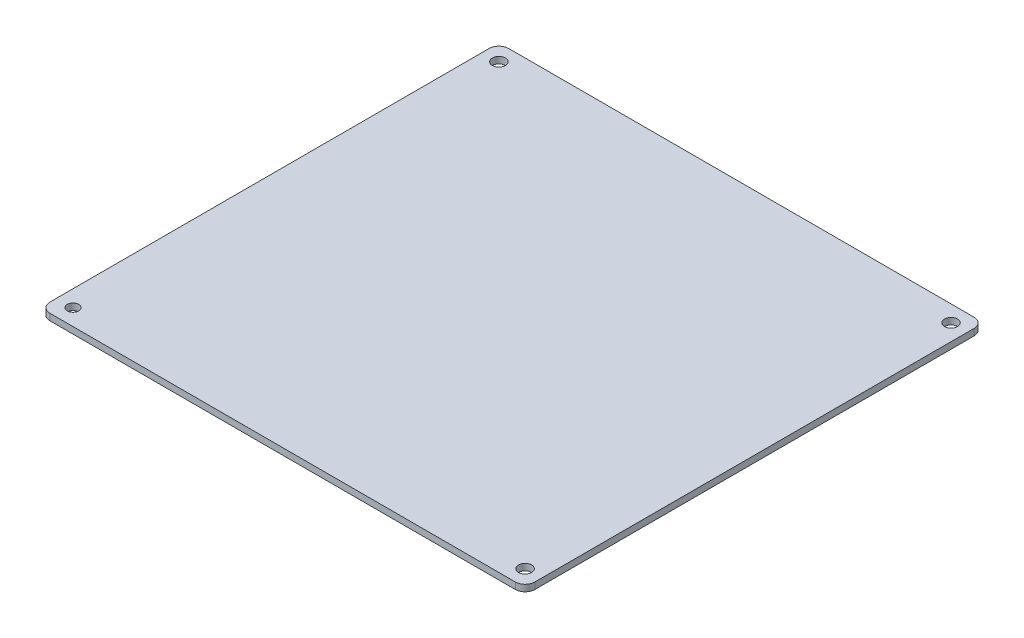
SolidWorks part; units mm, degrees
ref_plane "Front Plane" through (0, 0, 0) normal (0, 0, 1) x (1, 0, 0)
ref_plane "Top Plane" through (0, 0, 0) normal (0, 1, 0) x (1, 0, 0)
ref_plane "Right Plane" through (0, 0, 0) normal (1, 0, 0) x (0, 0, -1)
sketch "Sketch1" plane through (0, 0, 0) normal (0, 1, 0) x (1, 0, 0)
  line L1 (86.9141, 137.764) -> (-61.0859, 137.764)
  line L2 (86.9141, 137.764) -> (86.9141, -2.236)
  line L3 (86.9141, -2.236) -> (-61.0859, -2.236)
  line L4 (-61.0859, 137.764) -> (-61.0859, -2.236)
  dimension "D1" = 148
  dimension "D2" = 140
extrude "Boss-Extrude1" add sketch "Sketch1" along normal blind 2
sketch "Sketch2" plane through (0, 2, 0) normal (0, 1, 0) x (1, 0, 0)
  line L0 (86.9141, 137.764) -> (-61.0859, 137.764) construction
  line L1 (-61.0859, 137.764) -> (-61.0859, -2.236) construction
  line L2 (86.9141, -2.236) -> (86.9141, 137.764) construction
  line L3 (-61.0859, -2.236) -> (86.9141, -2.236) construction
  circle A0 centre (-56.0859, 132.764) radius 2
  circle A1 centre (81.9141, 132.764) radius 2
  circle A2 centre (81.9141, 2.764) radius 2
  circle A3 centre (-56.0859, 2.764) radius 1.7387
  point P0 (81.9141, 132.764)
  point P1 (81.9141, 2.764)
  point P2 (-56.0859, 2.764)
  point P3 (-56.0859, 132.764)
  point P20 (0, 0)
  dimension "D1" = 5
  dimension "D2" = 5
  dimension "D3" = 5
  dimension "D4" = 5
  dimension "D5" = 5
  dimension "D6" = 5
  dimension "D7" = 5
  dimension "D8" = 5
extrude "Cut-Extrude1" cut sketch "Sketch2" against normal blind 5
fillet "Fillet1" radius 3 1 edges at (86.9141, 1, 2.236)
fillet "Fillet2" radius 3 1 edges at (86.9141, 1, -137.764)
fillet "Fillet3" radius 3 1 edges at (-61.0859, 1, -137.764)
fillet "Fillet4" radius 3 1 edges at (-61.0859, 1, 2.236)
